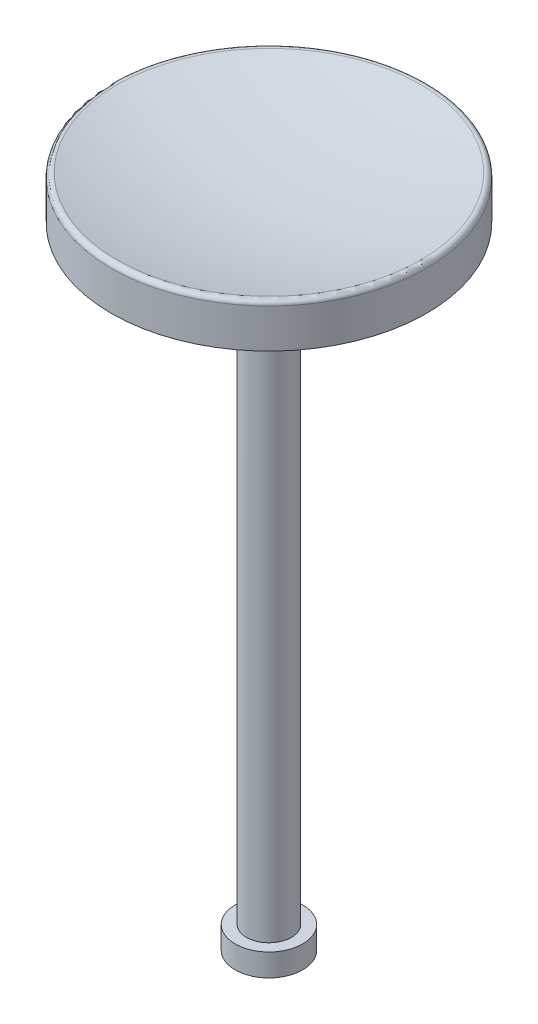
SolidWorks part; units mm, degrees
ref_plane "Front Plane" through (0, 0, 0) normal (0, 0, 1) x (1, 0, 0)
ref_plane "Top Plane" through (0, 0, 0) normal (0, 1, 0) x (1, 0, 0)
ref_plane "Right Plane" through (0, 0, 0) normal (1, 0, 0) x (0, 0, -1)
sketch "Sketch1" plane through (0, 0, 0) normal (0, 1, 0) x (1, 0, 0)
  circle A0 centre (0, 0) radius 6.35
  circle A1 centre (0, 0) radius 3.175
  dimension "D1" = 12.7
  dimension "D2" = 6.35
extrude "Boss-Extrude1" add sketch "Sketch1" along normal blind 177.8
sketch "Sketch6" plane through (0, 0, 0) normal (1, 0, 0) x (0, 0, -1)
  line L0 (0, 177.8) -> (-44.45, 177.8)
  line L1 (6.35, 177.8) -> (-6.35, 177.8) construction
  line L2 (-44.45, 177.8) -> (-44.45, 188.816)
  line L3 (0, 184.15) -> (0, 177.8)
  line L4 (0, 184.15) -> (-44.45, 184.15) construction
  arc A0 (-42.8373, 190.0389) -> (0, 184.15) centre (0, 342.9) ccw
  arc A1 (-44.45, 188.816) -> (-42.8373, 190.0389) centre (-43.18, 188.816) cw
  point P12 (-44.45, 190.5)
  dimension "D4" = 1.27
  dimension "D1" = 44.45
  dimension "D2" = 6.35
  dimension "D3" = 12.7
revolve "Revolve2" add sketch "Sketch6" angle 360 about L3
sketch "Sketch7" plane through (0, 0, 0) normal (0, -1, 0) x (1, 0, 0)
  circle A0 centre (0, 0) radius 9.525
  circle A1 centre (0, 0) radius 6.35
  dimension "D1" = 19.05
  dimension "D2" = 12.7
extrude "Boss-Extrude2" add sketch "Sketch7" against normal blind 6.35
